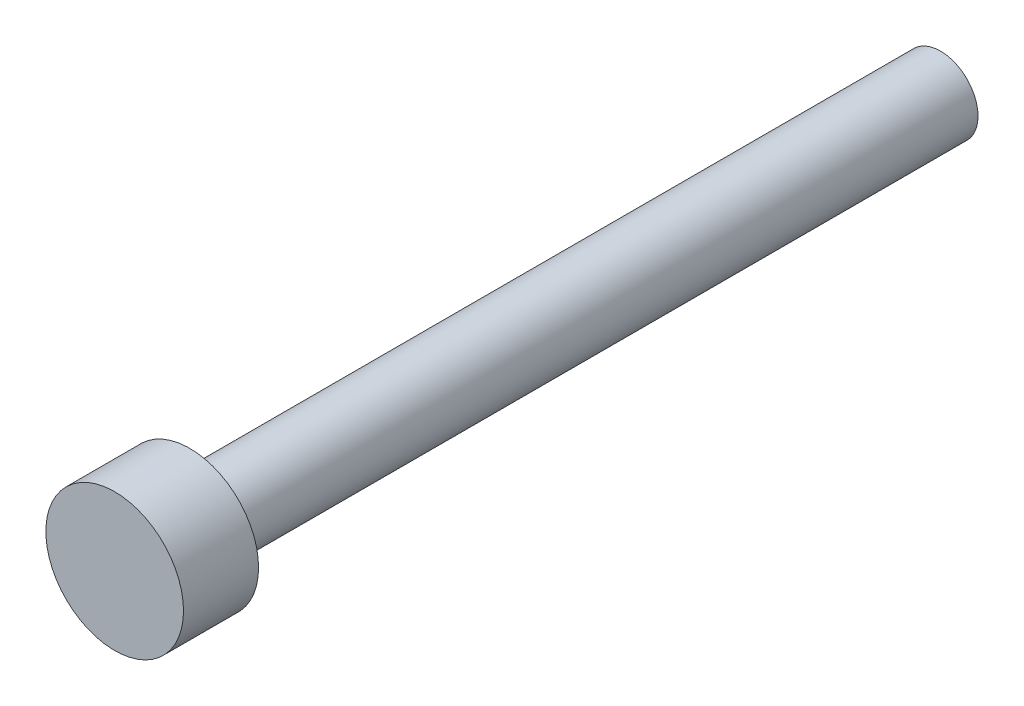
SolidWorks part; units mm, degrees
ref_plane "Front Plane" through (0, 0, 0) normal (0, 0, 1) x (1, 0, 0)
ref_plane "Top Plane" through (0, 0, 0) normal (0, 1, 0) x (1, 0, 0)
ref_plane "Right Plane" through (0, 0, 0) normal (1, 0, 0) x (0, 0, -1)
sketch "Shank_nominal_thread_envelope_profile" plane through (0, 0, 0) normal (0, 0, 1) x (1, 0, 0)
  circle A0 centre (0, 0) radius 1.5
  dimension "D1" = 3
extrude "Shank_nominal_thread_envelope" add sketch "Shank_nominal_thread_envelope_profile" along normal blind 30 from offset 30
sketch "Socket_head_envelope_profile" plane through (0, 0, 0) normal (0, 0, 1) x (1, 0, 0)
  circle A0 centre (0, 0) radius 2.75
  dimension "D1" = 5.5
extrude "Socket_head_envelope" add sketch "Socket_head_envelope_profile" along normal blind 3
